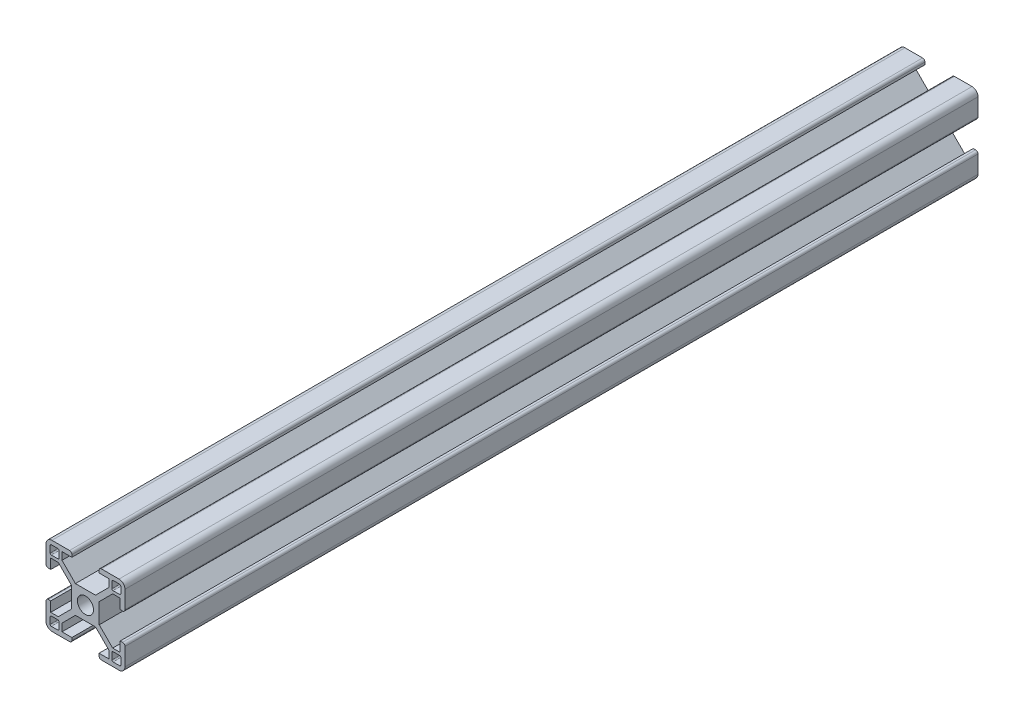
SolidWorks part; units mm, degrees
ref_plane "Alzado" through (0, 0, 0) normal (0, 0, 1) x (1, 0, 0)
ref_plane "Planta" through (0, 0, 0) normal (0, 1, 0) x (1, 0, 0)
ref_plane "Vista lateral" through (0, 0, 0) normal (1, 0, 0) x (0, 0, -1)
sketch "Croquis1" plane through (0, 0, 0) normal (0, 0, 1) x (1, 0, 0)
  line L0 (-16.0336, 5.4674) -> (-4.4336, 5.4674) construction
  line L1 (-4.4336, 1.2274) -> (-4.4336, 9.7074)
  line L2 (-4.4336, 9.7074) -> (1.2364, 15.3774)
  line L3 (1.2364, 15.3774) -> (4.4264, 15.3774)
  line L4 (4.4264, 15.3774) -> (4.4264, 11.1974)
  line L5 (4.4264, 11.1974) -> (5.4264, 11.1974)
  line L6 (6.4264, 12.1974) -> (6.4264, 19.6274)
  line L7 (-10.2336, 5.4674) -> (6.4264, 22.1274) construction
  line L8 (-4.5036, 20.1274) -> (-4.5036, 21.1274)
  line L9 (-3.5036, 22.1274) -> (3.9264, 22.1274)
  line L10 (-0.3236, 20.1274) -> (-4.5036, 20.1274)
  line L11 (-0.3236, 16.9374) -> (-0.3236, 20.1274)
  line L12 (-5.9936, 11.2674) -> (-0.3236, 16.9374)
  line L13 (-14.4736, 11.2674) -> (-5.9936, 11.2674)
  line L14 (-10.2336, 11.2674) -> (-10.2336, -0.3326) construction
  line L15 (1.4179, 20.3689) -> (4.1679, 20.3689)
  line L16 (0.9179, 19.8689) -> (0.9179, 17.1189)
  line L17 (1.4179, 16.6189) -> (4.1679, 16.6189)
  line L18 (4.6679, 19.8689) -> (4.6679, 17.1189)
  line L19 (0.9179, 20.3689) -> (4.6679, 16.6189) construction
  line L20 (0.9179, 16.6189) -> (4.6679, 20.3689) construction
  line L21 (-21.3851, 16.6189) -> (-25.1351, 20.3689) construction
  line L22 (-21.3851, 20.3689) -> (-25.1351, 16.6189) construction
  line L23 (-10.2336, 5.4674) -> (-26.8936, 22.1274) construction
  line L24 (-25.1351, 19.8689) -> (-25.1351, 17.1189)
  line L25 (-21.8851, 16.6189) -> (-24.6351, 16.6189)
  line L26 (-21.3851, 19.8689) -> (-21.3851, 17.1189)
  line L27 (-21.8851, 20.3689) -> (-24.6351, 20.3689)
  line L28 (-14.4736, 11.2674) -> (-20.1436, 16.9374)
  line L29 (-20.1436, 16.9374) -> (-20.1436, 20.1274)
  line L30 (-20.1436, 20.1274) -> (-15.9636, 20.1274)
  line L31 (-16.9636, 22.1274) -> (-24.3936, 22.1274)
  line L32 (-15.9636, 20.1274) -> (-15.9636, 21.1274)
  line L33 (-26.8936, 12.1974) -> (-26.8936, 19.6274)
  line L34 (-24.8936, 11.1974) -> (-25.8936, 11.1974)
  line L35 (-24.8936, 15.3774) -> (-24.8936, 11.1974)
  line L36 (-21.7036, 15.3774) -> (-24.8936, 15.3774)
  line L37 (-16.0336, 9.7074) -> (-21.7036, 15.3774)
  line L38 (-16.0336, 1.2274) -> (-16.0336, 9.7074)
  line L39 (-10.2336, 5.4674) -> (-26.8936, -11.1926) construction
  line L40 (-21.3851, -9.4341) -> (-25.1351, -5.6841) construction
  line L41 (-21.3851, -5.6841) -> (-25.1351, -9.4341) construction
  line L42 (0.9179, -5.6841) -> (4.6679, -9.4341) construction
  line L43 (0.9179, -9.4341) -> (4.6679, -5.6841) construction
  line L44 (-10.2336, 5.4674) -> (6.4264, -11.1926) construction
  line L45 (-16.0336, 1.2274) -> (-21.7036, -4.4426)
  line L46 (-21.7036, -4.4426) -> (-24.8936, -4.4426)
  line L47 (-24.8936, -4.4426) -> (-24.8936, -0.2626)
  line L48 (-24.8936, -0.2626) -> (-25.8936, -0.2626)
  line L49 (-26.8936, -1.2626) -> (-26.8936, -8.6926)
  line L50 (-15.9636, -9.1926) -> (-15.9636, -10.1926)
  line L51 (-16.9636, -11.1926) -> (-24.3936, -11.1926)
  line L52 (-20.1436, -9.1926) -> (-15.9636, -9.1926)
  line L53 (-20.1436, -6.0026) -> (-20.1436, -9.1926)
  line L54 (-14.4736, -0.3326) -> (-20.1436, -6.0026)
  line L55 (-21.8851, -9.4341) -> (-24.6351, -9.4341)
  line L56 (-21.3851, -8.9341) -> (-21.3851, -6.1841)
  line L57 (-21.8851, -5.6841) -> (-24.6351, -5.6841)
  line L58 (-25.1351, -8.9341) -> (-25.1351, -6.1841)
  line L59 (4.6679, -8.9341) -> (4.6679, -6.1841)
  line L60 (1.4179, -5.6841) -> (4.1679, -5.6841)
  line L61 (0.9179, -8.9341) -> (0.9179, -6.1841)
  line L62 (1.4179, -9.4341) -> (4.1679, -9.4341)
  line L63 (-14.4736, -0.3326) -> (-5.9936, -0.3326)
  line L64 (-5.9936, -0.3326) -> (-0.3236, -6.0026)
  line L65 (-0.3236, -6.0026) -> (-0.3236, -9.1926)
  line L66 (-0.3236, -9.1926) -> (-4.5036, -9.1926)
  line L67 (-3.5036, -11.1926) -> (3.9264, -11.1926)
  line L68 (-4.5036, -9.1926) -> (-4.5036, -10.1926)
  line L69 (6.4264, -1.2626) -> (6.4264, -8.6926)
  line L70 (4.4264, -0.2626) -> (5.4264, -0.2626)
  line L71 (4.4264, -4.4426) -> (4.4264, -0.2626)
  line L72 (1.2364, -4.4426) -> (4.4264, -4.4426)
  line L73 (-4.4336, 1.2274) -> (1.2364, -4.4426)
  arc A0 (5.4264, 11.1974) -> (6.4264, 12.1974) centre (5.4264, 12.1974) ccw
  arc A1 (6.4264, 19.6274) -> (3.9264, 22.1274) centre (3.9264, 19.6274) ccw
  arc A2 (-4.5036, 21.1274) -> (-3.5036, 22.1274) centre (-3.5036, 21.1274) cw
  arc A3 (0.9179, 17.1189) -> (1.4179, 16.6189) centre (1.4179, 17.1189) ccw
  arc A4 (4.1679, 16.6189) -> (4.6679, 17.1189) centre (4.1679, 17.1189) ccw
  arc A5 (4.1679, 20.3689) -> (4.6679, 19.8689) centre (4.1679, 19.8689) cw
  arc A6 (1.4179, 20.3689) -> (0.9179, 19.8689) centre (1.4179, 19.8689) ccw
  arc A7 (-21.8851, 20.3689) -> (-21.3851, 19.8689) centre (-21.8851, 19.8689) cw
  arc A8 (-24.6351, 20.3689) -> (-25.1351, 19.8689) centre (-24.6351, 19.8689) ccw
  arc A9 (-24.6351, 16.6189) -> (-25.1351, 17.1189) centre (-24.6351, 17.1189) cw
  arc A10 (-21.3851, 17.1189) -> (-21.8851, 16.6189) centre (-21.8851, 17.1189) cw
  arc A11 (-15.9636, 21.1274) -> (-16.9636, 22.1274) centre (-16.9636, 21.1274) ccw
  arc A12 (-26.8936, 19.6274) -> (-24.3936, 22.1274) centre (-24.3936, 19.6274) cw
  arc A13 (-25.8936, 11.1974) -> (-26.8936, 12.1974) centre (-25.8936, 12.1974) cw
  arc A14 (-25.8936, -0.2626) -> (-26.8936, -1.2626) centre (-25.8936, -1.2626) ccw
  arc A15 (-26.8936, -8.6926) -> (-24.3936, -11.1926) centre (-24.3936, -8.6926) ccw
  arc A16 (-15.9636, -10.1926) -> (-16.9636, -11.1926) centre (-16.9636, -10.1926) cw
  arc A17 (-21.3851, -6.1841) -> (-21.8851, -5.6841) centre (-21.8851, -6.1841) ccw
  arc A18 (-24.6351, -5.6841) -> (-25.1351, -6.1841) centre (-24.6351, -6.1841) ccw
  arc A19 (-24.6351, -9.4341) -> (-25.1351, -8.9341) centre (-24.6351, -8.9341) cw
  arc A20 (-21.8851, -9.4341) -> (-21.3851, -8.9341) centre (-21.8851, -8.9341) ccw
  arc A21 (1.4179, -9.4341) -> (0.9179, -8.9341) centre (1.4179, -8.9341) cw
  arc A22 (4.1679, -9.4341) -> (4.6679, -8.9341) centre (4.1679, -8.9341) ccw
  arc A23 (4.1679, -5.6841) -> (4.6679, -6.1841) centre (4.1679, -6.1841) cw
  arc A24 (0.9179, -6.1841) -> (1.4179, -5.6841) centre (1.4179, -6.1841) cw
  arc A25 (-4.5036, -10.1926) -> (-3.5036, -11.1926) centre (-3.5036, -10.1926) ccw
  arc A26 (6.4264, -8.6926) -> (3.9264, -11.1926) centre (3.9264, -8.6926) cw
  arc A27 (5.4264, -0.2626) -> (6.4264, -1.2626) centre (5.4264, -1.2626) cw
  circle A28 centre (-10.2336, 5.4674) radius 3.4
  point P21 (2.7929, 18.4939)
  point P73 (-23.2601, 18.4939)
  point P74 (-15.9636, 22.1274)
  point P75 (-26.8936, 11.1974)
  point P145 (-26.8936, -0.2626)
  point P146 (-15.9636, -11.1926)
  point P147 (-23.2601, -7.5591)
  point P148 (2.7929, -7.5591)
  point P149 (-4.5036, -11.1926)
  point P150 (6.4264, -0.2626)
  dimension "D6" = 1
  dimension "D7" = 1
  dimension "D10" = 0.5
  dimension "D11" = 6.8
  dimension "D1" = 4.24
  dimension "D2" = 5.67
  dimension "D3" = 3.19
  dimension "D4" = 4.18
  dimension "D5" = 135
  dimension "D8" = 3.75
  dimension "D9" = 3.75
extrude "Saliente-Extruir1" add sketch "Croquis1" along normal blind 360
